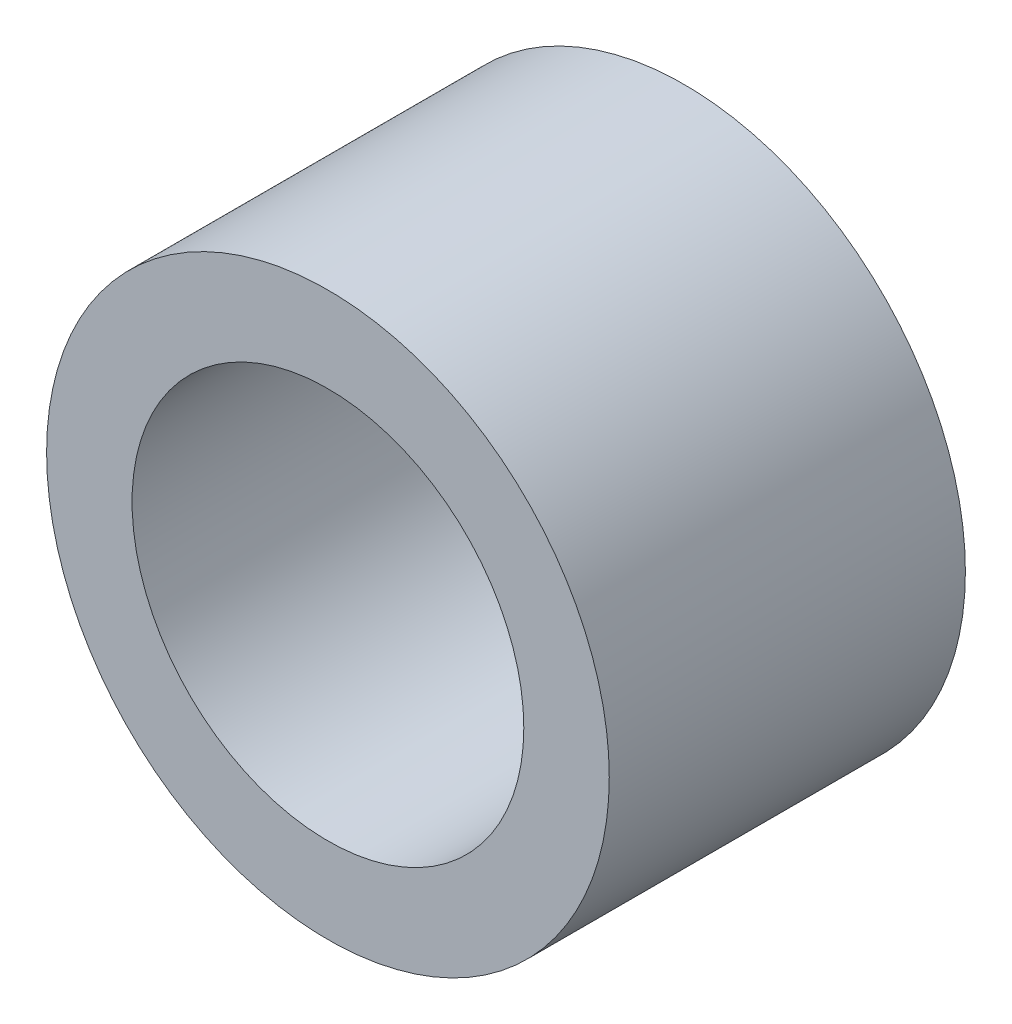
SolidWorks part; units mm, degrees
ref_plane "Front Plane" through (0, 0, 0) normal (0, 0, 1) x (1, 0, 0)
ref_plane "Top Plane" through (0, 0, 0) normal (0, 1, 0) x (1, 0, 0)
ref_plane "Right Plane" through (0, 0, 0) normal (1, 0, 0) x (0, 0, -1)
sketch "Sketch1" plane through (0, 0, 0) normal (0, 0, 1) x (1, 0, 0)
  circle A0 centre (0, 0) radius 3.95
  dimension "D1" = 7.9
extrude "Boss-Extrude1" add sketch "Sketch1" along normal blind 5
sketch "Sketch2" plane through (0, 0, 5) normal (0, 0, 1) x (1, 0, 0)
  circle A0 centre (0, 0) radius 2.75
  dimension "D1" = 5.5
extrude "Cut-Extrude1" cut sketch "Sketch2" against normal blind 5
